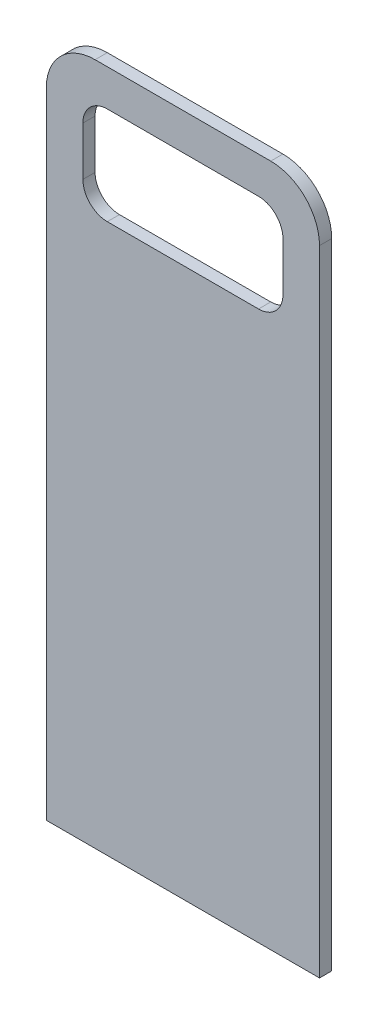
SolidWorks part; units mm, degrees
material "Maple"
ref_plane "Front Plane" through (0, 0, 0) normal (0, 0, 1) x (1, 0, 0)
ref_plane "Top Plane" through (0, 0, 0) normal (0, 1, 0) x (1, 0, 0)
ref_plane "Right Plane" through (0, 0, 0) normal (1, 0, 0) x (0, 0, -1)
sketch "Sketch1" plane through (0, 0, 0) normal (0, 0, 1) x (1, 0, 0)
  line L1 (0, 0) -> (-112, 0)
  line L2 (0, 0) -> (0, 280)
  line L3 (0, 280) -> (-112, 280)
  line L4 (-112, 0) -> (-112, 280)
  line L5 (-15, 265) -> (-97, 265)
  line L6 (-15, 265) -> (-15, 225)
  line L7 (-15, 225) -> (-97, 225)
  line L8 (-97, 265) -> (-97, 225)
  dimension "D1" = 280
  dimension "D2" = 112
  dimension "D3" = 40
  dimension "D4" = 15
  dimension "D5" = 15
  dimension "D6" = 15
extrude "Boss-Extrude1" add sketch "Sketch1" along normal blind 5
fillet "Fillet1" radius 20 2 edges at (-112, 280, 2.5) (0, 280, 2.5)
fillet "Fillet2" radius 10 4 edges at (-97, 225, 2.5) (-97, 265, 2.5) (-15, 225, 2.5) (-15, 265, 2.5)
